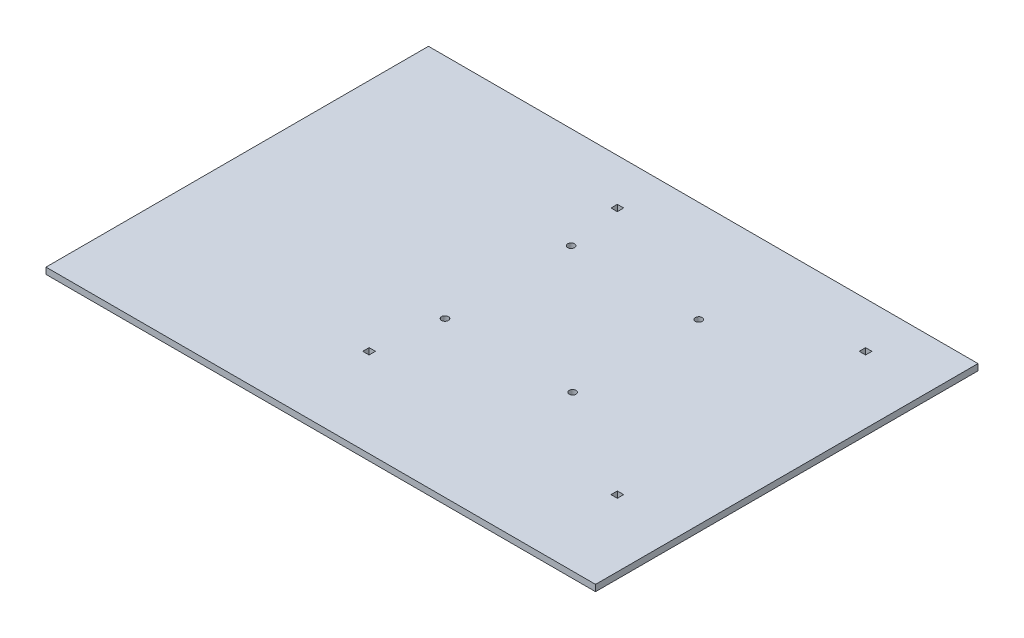
SolidWorks part; units mm, degrees
ref_plane "Front Plane" through (0, 0, 0) normal (0, 0, 1) x (1, 0, 0)
ref_plane "Top Plane" through (0, 0, 0) normal (0, 1, 0) x (1, 0, 0)
ref_plane "Right Plane" through (0, 0, 0) normal (1, 0, 0) x (0, 0, -1)
sketch "Sketch1" plane through (0, 0, 0) normal (0, 1, 0) x (1, 0, 0)
  line L1 (-70, -80) -> (70, -80)
  line L2 (-70, -80) -> (-70, 80)
  line L3 (-70, 80) -> (70, 80)
  line L4 (70, -80) -> (70, 80)
  line L5 (-70, -80) -> (70, 80) construction
  line L6 (-70, 80) -> (70, -80) construction
  point P0 (0, 0)
  dimension "D1" = 140
  dimension "D2" = 160
extrude "Boss-Extrude1" add sketch "Sketch1" along normal blind 3
sketch "Sketch2" plane through (0, 3, 0) normal (0, 1, 0) x (1, 0, 0)
  line L1 (-57, -57) -> (57, -57)
  line L2 (-57, -57) -> (-57, 57)
  line L3 (-57, 57) -> (57, 57)
  line L4 (57, -57) -> (57, 57)
  line L5 (-57, -57) -> (57, 57) construction
  line L6 (-57, 57) -> (57, -57) construction
  line L7 (60, -60) -> (-60, -60)
  line L8 (60, -60) -> (60, 60)
  line L9 (60, 60) -> (-60, 60)
  line L10 (-60, -60) -> (-60, 60)
  line L11 (60, -60) -> (-60, 60) construction
  line L12 (60, 60) -> (-60, -60) construction
  point P0 (0, 0)
  point P6 (0, 0)
  dimension "D1" = 114
  dimension "D2" = 114
  dimension "D3" = 120
extrude "Boss-Extrude2" add sketch "Sketch2" along normal blind 70
sketch "Sketch4" plane through (0, 73, 0) normal (0, 1, 0) x (1, 0, 0)
  line L1 (-60, 60) -> (60, 60)
  line L2 (-60, 60) -> (-60, -60)
  line L3 (-60, -60) -> (60, -60)
  line L4 (60, 60) -> (60, -60)
  dimension "D1" = 120
  dimension "D2" = 120
extrude "Boss-Extrude4" add sketch "Sketch4" along normal blind 3
sketch "Sketch5" plane through (0, 76, 0) normal (0, 1, 0) x (1, 0, 0)
  line L0 (-60, 60) -> (60, -60) construction
  line L1 (-10.27, -9.855) -> (29.63, -9.855)
  line L2 (-10.27, -9.855) -> (-10.27, 9.855)
  line L3 (-10.27, 9.855) -> (29.63, 9.855)
  line L4 (29.63, -9.855) -> (29.63, 9.855)
  line L5 (-10.27, -9.855) -> (29.63, 9.855) construction
  line L6 (-10.27, 9.855) -> (29.63, -9.855) construction
  line L7 (60, -60) -> (60, 60) construction
  line L8 (60, -60) -> (60, 60) construction
  line L9 (60, -60) -> (60, 60) construction
  line L10 (60, 60) -> (-60, 60) construction
  line L11 (60, 60) -> (-60, -60) construction
  circle A1 centre (34.39, -4.925) radius 2.1
  circle A2 centre (34.39, 4.925) radius 2.1
  circle A4 centre (-15.03, -4.925) radius 2.1
  circle A5 centre (-15.03, 4.925) radius 2.1
  point P3 (9.68, 0)
  dimension "D2" = 4.2
  dimension "D6" = 9.85
  dimension "D7" = 4.93
  dimension "D8" = 4.93
  dimension "D9" = 4.93
  dimension "D10" = 9.68
  dimension "D11" = 4.93
  dimension "D12" = 4.93
  dimension "D1" = 39.9
  dimension "D3" = 19.71
  dimension "D4" = 4.76
  dimension "D5" = 4.76
extrude "Cut-Extrude2" cut sketch "Sketch5" against normal blind 3
sketch "Sketch6" plane through (0, 76, 0) normal (0, 1, 0) x (1, 0, 0)
  line L1 (9.1491, -8.655) -> (-9.1491, -8.655)
  line L2 (9.1491, -8.655) -> (9.1491, 8.655)
  line L3 (9.1491, 8.655) -> (-9.1491, 8.655)
  line L4 (-9.1491, -8.655) -> (-9.1491, 8.655)
  line L5 (9.1491, -8.655) -> (-9.1491, 8.655) construction
  line L6 (9.1491, 8.655) -> (-9.1491, -8.655) construction
  point P0 (0, 0)
extrude "Cut-Extrude3" cut sketch "Sketch6" against normal blind 3
sketch "Sketch7" plane through (0, 0, 0) normal (0, 1, 0) x (1, 0, 0)
  line L1 (-45, -45) -> (45, -45)
  line L2 (-45, -45) -> (-45, 45)
  line L3 (-45, 45) -> (45, 45)
  line L4 (45, -45) -> (45, 45)
  line L5 (-45, -45) -> (45, 45) construction
  line L6 (-45, 45) -> (45, -45) construction
  point P0 (0, 0)
  dimension "D1" = 90
  dimension "D2" = 90
sketch "Sketch13" plane through (0, 76, 0) normal (0, 1, 0) x (1, 0, 0)
  arc A0 (-3.7926, 43.0768) -> (-0.8101, -42.9734) centre (-3.7926, 0) ccw construction
  arc A1 (-3.7926, 49.7288) -> (-0.3495, -49.6094) centre (-3.7926, 0) ccw
  arc A2 (-3.7926, 36.4249) -> (-1.2706, -36.3375) centre (-3.7926, 0) ccw
  arc A3 (-3.7926, 36.4249) -> (-3.7926, 49.7288) centre (-3.7926, 43.0768) ccw
  arc A4 (-0.3495, -49.6094) -> (-1.2706, -36.3375) centre (-0.8101, -42.9734) ccw
  point P3 (-46.8436, -1.4922)
extrude "Cut-Extrude8" cut sketch "Sketch13" against normal blind 5
sketch "Sketch15" plane through (0, 3, 0) normal (0, 1, 0) x (1, 0, 0)
  line L0 (70, 80) -> (-70, 80) construction
  line L1 (90, 80) -> (-169.0216, 80)
  line L2 (90, 80) -> (90, -100.2694)
  line L3 (90, -100.2694) -> (-169.0216, -100.2694)
  line L4 (-169.0216, 80) -> (-169.0216, -100.2694)
extrude "Boss-Extrude5" add sketch "Sketch15" against normal blind 3
sketch "Sketch18" plane through (0, 3, 0) normal (0, 1, 0) x (1, 0, 0)
  line L0 (-57, 57) -> (57, 57) construction
  line L1 (-57, -57) -> (-57, 57) construction
  circle A0 centre (-55.452, -27.2274) radius 1.6 construction
  circle A2 centre (-55.452, 32.2086) radius 1.6 construction
  circle A4 centre (-54, -27.2314) radius 1.6
  circle A6 centre (6.2, -27.2314) radius 1.6
  circle A8 centre (-54, 32.2086) radius 1.6
  circle A9 centre (6.2, 32.2086) radius 1.6
  point P10 (0, 0)
  point P11 (0, 0)
  point P13 (0, 0)
  point P17 (0, 0)
  point P20 (0, 0)
  dimension "D2" = 3.2
  dimension "D6" = 59.44
  dimension "D7" = 60.2
  dimension "D1" = 59.436
  dimension "D3" = 3
  dimension "D4" = 3
  dimension "D5" = 24.7914
extrude "Cut-Extrude9" cut sketch "Sketch18" against normal blind 10
sketch "Sketch19" plane through (-60, 0, 0) normal (-1, 0, 0) x (0, 0, 1)
  line L0 (12.3674, 3) -> (12.3674, 33) construction
  line L1 (-60, 3) -> (60, 3) construction
  line L2 (-5.6466, 31.35) -> (-5.6466, 26.9) construction
  line L3 (6.3674, 30.75) -> (18.3674, 30.75)
  line L4 (6.3674, 30.75) -> (6.3674, 35.25)
  line L5 (6.3674, 35.25) -> (18.3674, 35.25)
  line L6 (18.3674, 30.75) -> (18.3674, 35.25)
  line L7 (6.3674, 30.75) -> (18.3674, 35.25) construction
  line L8 (6.3674, 35.25) -> (18.3674, 30.75) construction
  line L9 (-5.2594, 33) -> (-5.2594, 41.4) construction
  line L10 (-5.2594, 33) -> (-17.2594, 33) construction
  line L11 (-5.2594, 41.4) -> (-17.2594, 41.4) construction
  line L12 (-17.2594, 33) -> (-17.2594, 41.4) construction
  line L13 (-33.6488, 33.0619) -> (-23.5648, 33.0619) construction
  line L14 (-28.1126, 38.85) -> (-28.1126, 27.45) construction
  line L15 (-23.5648, 40.424) -> (-23.5648, 33.0619) construction
  line L16 (-33.6488, 40.424) -> (-23.5648, 40.424) construction
  line L17 (-33.6488, 40.424) -> (-33.6488, 33.0619) construction
  line L18 (-5.2594, 33) -> (-5.2594, 41.4)
  line L19 (-5.2594, 33) -> (-17.2594, 33)
  line L20 (-5.2594, 41.4) -> (-17.2594, 41.4)
  line L21 (-17.2594, 33) -> (-17.2594, 41.4)
  line L22 (-33.6488, 33.0619) -> (-23.5648, 33.0619)
  line L23 (-28.1126, 38.85) -> (-28.1126, 27.45)
  line L24 (-23.5648, 40.424) -> (-23.5648, 33.0619)
  line L25 (-33.6488, 40.424) -> (-23.5648, 40.424)
  line L26 (-33.6488, 40.424) -> (-33.6488, 33.0619)
  dimension "D1" = 14.86
  dimension "D2" = 30
  dimension "D3" = 4.5
  dimension "D4" = 90
  dimension "D5" = 12
extrude "Cut-Extrude11" cut sketch "Sketch19" against normal blind 5
sketch "Sketch20" plane through (60, 0, 0) normal (1, 0, 0) x (0, 0, -1)
  line L0 (-100.2694, 3) -> (80, 3) construction
  line L1 (-79.3696, 96.2468) -> (68.0462, 96.2468)
  line L2 (-79.3696, 96.2468) -> (-79.3696, 3)
  line L3 (-79.3696, 3) -> (68.0462, 3)
  line L4 (68.0462, 96.2468) -> (68.0462, 3)
extrude "Cut-Extrude13" cut sketch "Sketch20" against normal through all
sketch "Sketch21" plane through (0, 3, 0) normal (0, 1, 0) x (1, 0, 0)
  line L1 (-60, 60) -> (-57, 60)
  line L2 (-60, 60) -> (-60, 57)
  line L3 (-60, 57) -> (-57, 57)
  line L4 (-57, 60) -> (-57, 57)
  line L5 (60, -60) -> (57, -60)
  line L6 (60, -60) -> (60, -57)
  line L7 (60, -57) -> (57, -57)
  line L8 (57, -60) -> (57, -57)
  line L9 (60, 60) -> (57, 60)
  line L10 (60, 60) -> (60, 57)
  line L11 (60, 57) -> (57, 57)
  line L12 (57, 60) -> (57, 57)
  line L13 (-60, -60) -> (-57, -60)
  line L14 (-60, -60) -> (-60, -57)
  line L15 (-60, -57) -> (-57, -57)
  line L16 (-57, -60) -> (-57, -57)
extrude "Cut-Extrude14" cut sketch "Sketch21" against normal through all contours L2 L1 L4 L3 | L14 L13 L16 L15 | L6 L5 L8 L7 | L10 L9 L12 L11
